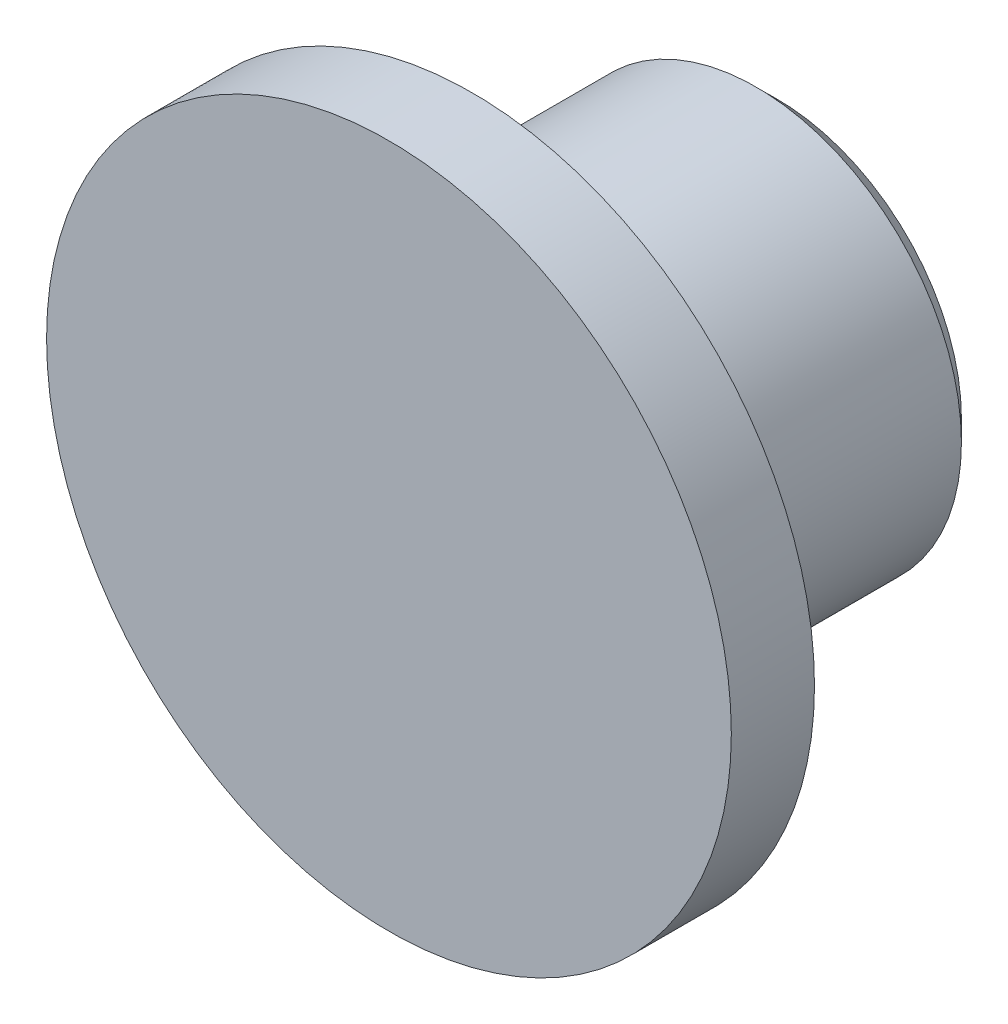
SolidWorks part; units mm, degrees
material "7075-T6 (SN)"
ref_plane "前视基准面" through (0, 0, 0) normal (0, 0, 1) x (1, 0, 0)
ref_plane "上视基准面" through (0, 0, 0) normal (0, 1, 0) x (1, 0, 0)
ref_plane "右视基准面" through (0, 0, 0) normal (1, 0, 0) x (0, 0, -1)
ref_plane "基准面1" through (0, 0, -54.804) normal (0, 0, 1) x (1, 0, 0)
sketch "草图1" plane through (0, 0, -54.804) normal (0, 0, 1) x (1, 0, 0)
  circle A0 centre (-14.8535, -1.5241) radius 2.47
extrude "凸台-拉伸1" add sketch "草图1" along normal up to surface (0.6 mm away)
sketch "草图2" plane through (0, 0, -54.804) normal (0, 0, 1) x (1, 0, 0)
  circle A0 centre (-14.8535, -1.5241) radius 1.48
extrude "凸台-拉伸2" add sketch "草图2" against normal blind 2.2
chamfer "倒角1" distance 0.15 angle 45 1 edges at (-13.3735, -1.5241, -57.004)
